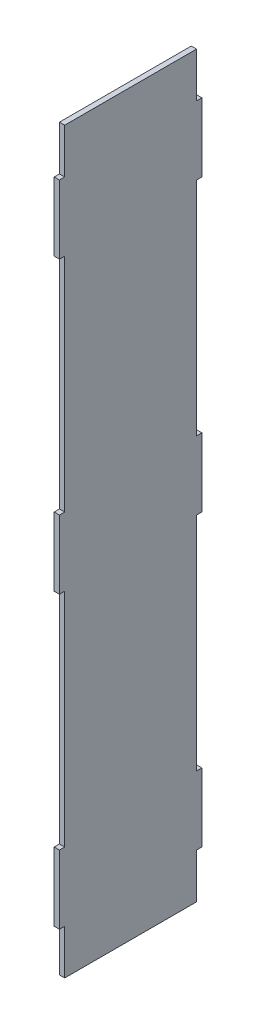
SolidWorks part; units mm, degrees
ref_plane "Front Plane" through (0, 0, 0) normal (0, 0, 1) x (1, 0, 0)
ref_plane "Top Plane" through (0, 0, 0) normal (0, 1, 0) x (1, 0, 0)
ref_plane "Right Plane" through (0, 0, 0) normal (1, 0, 0) x (0, 0, -1)
sketch "Sketch1" plane through (0, 0, 0) normal (1, 0, 0) x (0, 0, -1)
  line L0 (-12.5, 61.5) -> (-13.5, 61.5)
  line L1 (-12.5, -70) -> (12.5, -70)
  line L2 (-12.5, -70) -> (-12.5, 70) construction
  line L3 (-12.5, 70) -> (12.5, 70)
  line L4 (12.5, -70) -> (12.5, 70) construction
  line L5 (-12.5, -70) -> (12.5, 70) construction
  line L6 (-12.5, 70) -> (12.5, -70) construction
  line L7 (-13.5, 61.5) -> (-13.5, 48.5)
  line L8 (-13.5, 48.5) -> (-12.5, 48.5)
  line L9 (-12.5, 48.5) -> (-12.5, 6.5)
  line L10 (-12.5, 6.5) -> (-13.5, 6.5)
  line L11 (-13.5, 6.5) -> (-13.5, -6.5)
  line L12 (-13.5, -6.5) -> (-12.5, -6.5)
  line L13 (-12.5, -6.5) -> (-12.5, -48.5)
  line L14 (-12.5, -48.5) -> (-13.5, -48.5)
  line L15 (-13.5, -48.5) -> (-13.5, -61.5)
  line L16 (-13.5, -61.5) -> (-12.5, -61.5)
  line L17 (-12.5, -61.5) -> (-12.5, -70)
  line L18 (-12.5, 61.5) -> (-12.5, 70)
  line L19 (-13.5, 0) -> (0, 0) construction
  line L20 (0, 75) -> (0, -75) construction
  line L21 (12.5, -61.5) -> (12.5, -70)
  line L22 (13.5, -61.5) -> (12.5, -61.5)
  line L23 (13.5, -48.5) -> (13.5, -61.5)
  line L24 (12.5, -48.5) -> (13.5, -48.5)
  line L25 (12.5, -6.5) -> (12.5, -48.5)
  line L26 (13.5, -6.5) -> (12.5, -6.5)
  line L27 (13.5, 6.5) -> (13.5, -6.5)
  line L28 (12.5, 6.5) -> (13.5, 6.5)
  line L29 (12.5, 48.5) -> (12.5, 6.5)
  line L30 (13.5, 48.5) -> (12.5, 48.5)
  line L31 (13.5, 61.5) -> (13.5, 48.5)
  line L32 (12.5, 61.5) -> (13.5, 61.5)
  line L33 (12.5, 61.5) -> (12.5, 70)
  line L34 (13.5, 55) -> (24.0974, 55) construction
  line L35 (24.0974, -55) -> (24.0974, 0) construction
  line L36 (24.0974, -55) -> (13.5, -55) construction
  line L37 (13.5, 0) -> (24.0974, 0) construction
  line L38 (24.0974, 0) -> (24.0974, 55) construction
  circle A0 centre (0, -75) radius 12.5 construction
  circle A1 centre (0, 75) radius 12.5 construction
  circle A2 centre (0, -75) radius 2.5 construction
  circle A3 centre (0, 75) radius 2.5 construction
  point P0 (0, 0)
  point P25 (-13.5, 55)
  dimension "D6" = 25
  dimension "D7" = 5
  dimension "D1" = 5
  dimension "D2" = 13
  dimension "D3" = 150
  dimension "D4" = 55
  dimension "D5" = 20
  dimension "D8" = 1
  dimension "D9" = 25
  dimension "D10" = 55
extrude "Boss-Extrude1" add sketch "Sketch1" along normal blind 1
